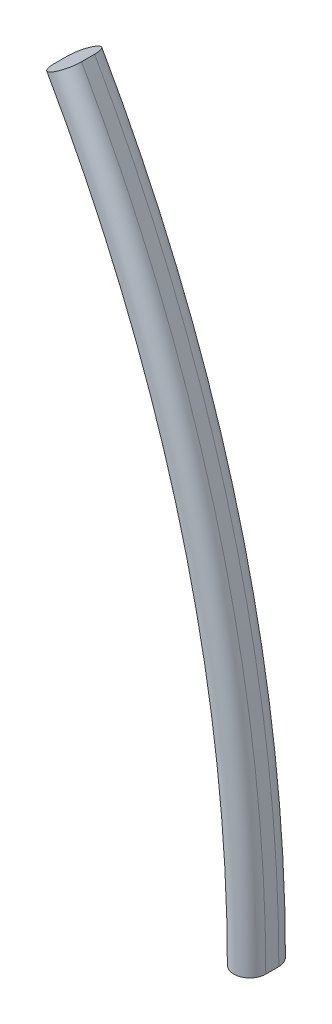
SolidWorks part; units mm, degrees
ref_plane "Front Plane" through (0, 0, 0) normal (0, 0, 1) x (1, 0, 0)
ref_plane "Top Plane" through (0, 0, 0) normal (0, 1, 0) x (1, 0, 0)
ref_plane "Right Plane" through (0, 0, 0) normal (1, 0, 0) x (0, 0, -1)
sketch "Sketch1" plane through (0, 0, 0) normal (0, 1, 0) x (1, 0, 0)
  line L3 (0, -2.1) -> (0, 2.1) construction
  line L4 (-5.125, -2.1) -> (-5.125, 2.1)
  line L5 (5.125, -2.1) -> (5.125, 2.1)
  arc A2 (-5.125, -2.1) -> (5.125, -2.1) centre (0, -2.1) ccw
  arc A3 (5.125, 2.1) -> (-5.125, 2.1) centre (0, 2.1) ccw
  point P0 (0, 0)
  point P10 (0, 0)
  point P15 (0, 0)
  dimension "D3" = 10.25
  dimension "D4" = 4.2
sketch "Sketch3" plane through (0, 0, 0) normal (0, 0, 1) x (1, 0, 0)
  line L0 (0, 0) -> (0, 220) construction
  line L1 (0, 220) -> (-58.5941, 222.0392) construction
  line L2 (-450, 0) -> (-58.5941, 222.0392) construction
  arc A0 (0, 0) -> (-58.5941, 222.0392) centre (-450, 0) ccw
  point P0 (-2, 0)
  dimension "D1" = 900
  dimension "D2" = 220
sweep "Sweep1" add profiles "Sketch1" path "Sketch3"
shell "Shell3" thickness 0.4
